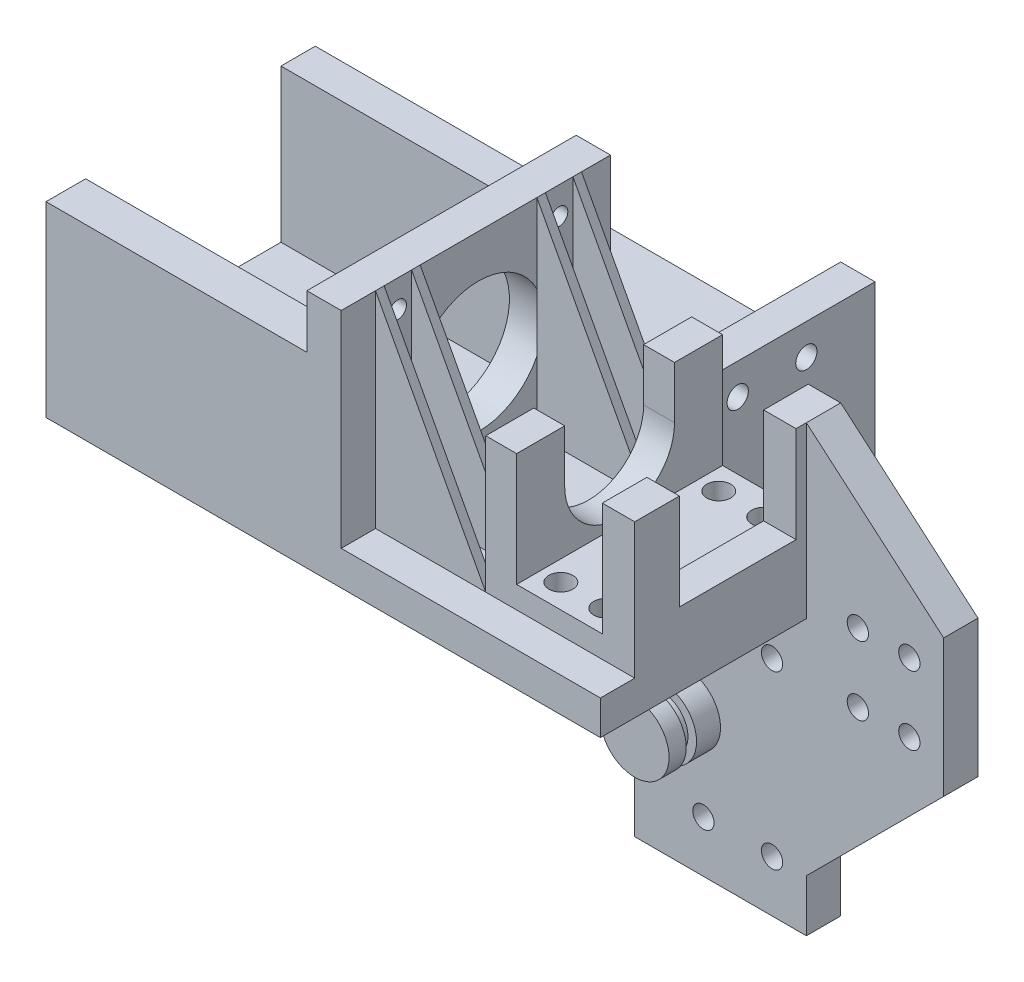
SolidWorks part; units mm, degrees
ref_plane "Front Plane" through (0, 0, 0) normal (0, 0, 1) x (1, 0, 0)
ref_plane "Top Plane" through (0, 0, 0) normal (0, 1, 0) x (1, 0, 0)
ref_plane "Right Plane" through (0, 0, 0) normal (1, 0, 0) x (0, 0, -1)
sketch "Sketch1" plane through (0, 0, 0) normal (0, 1, 0) x (1, 0, 0)
  line L0 (0, 0) -> (161.51, 0)
  line L1 (161.51, 0) -> (161.51, 70)
  line L2 (161.51, 70) -> (121.51, 70)
  line L3 (121.51, 70) -> (121.51, 120)
  line L4 (121.51, 120) -> (0, 120)
  line L5 (0, 120) -> (0, 0)
  dimension "D1" = 40
  dimension "D2" = 161.51
  dimension "D3" = 70
  dimension "D4" = 120
extrude "Boss-Extrude1" add sketch "Sketch1" along normal blind 10
sketch "Sketch2" plane through (0, 10, 0) normal (0, 1, 0) x (1, 0, 0)
  line L1 (161.51, 70) -> (152.06, 70)
  line L2 (161.51, 70) -> (161.51, 10)
  line L3 (161.51, 10) -> (152.06, 10)
  line L4 (152.06, 70) -> (152.06, 10)
  line L5 (0, 0) -> (161.51, 0) construction
  dimension "D1" = 9.45
  dimension "D2" = 10
extrude "Boss-Extrude2" add sketch "Sketch2" along normal blind 39.45
sketch "Sketch3" plane through (0, 10, 0) normal (0, 1, 0) x (1, 0, 0)
  line L1 (152.06, 70) -> (127.1, 70)
  line L2 (152.06, 70) -> (152.06, 10)
  line L3 (152.06, 10) -> (127.1, 10)
  line L4 (127.1, 70) -> (127.1, 10)
  line L5 (0, 0) -> (161.51, 0) construction
  dimension "D1" = 24.96
  dimension "D2" = 10
extrude "Boss-Extrude3" add sketch "Sketch3" along normal blind 6.45
sketch "Sketch4" plane through (0, 10, 0) normal (0, 1, 0) x (1, 0, 0)
  line L1 (127.1, 70) -> (118.1, 70)
  line L2 (127.1, 70) -> (127.1, 10)
  line L3 (127.1, 10) -> (118.1, 10)
  line L4 (118.1, 70) -> (118.1, 10)
  line L5 (0, 0) -> (161.51, 0) construction
  dimension "D1" = 9
  dimension "D2" = 10
extrude "Boss-Extrude4" add sketch "Sketch4" along normal blind 39.45
sketch "Sketch5" plane through (161.51, 0, 0) normal (1, 0, 0) x (0, 0, -1)
  line L0 (10, 49.45) -> (70, 49.45) construction
  line L1 (23, 49.45) -> (57, 49.45)
  line L2 (23, 49.45) -> (23, 21.45)
  line L3 (23, 21.45) -> (57, 21.45)
  line L4 (57, 49.45) -> (57, 21.45)
  line L5 (10, 49.45) -> (10, 10) construction
  point P11 (30, 49.45)
  dimension "D1" = 34
  dimension "D2" = 28
  dimension "D3" = 13
extrude "Cut-Extrude1" cut sketch "Sketch5" against normal up to next
sketch "Sketch6" plane through (127.1, 0, 0) normal (1, 0, 0) x (0, 0, -1)
  line L0 (24, 49.45) -> (24, 34.24)
  line L1 (10, 49.45) -> (70, 49.45) construction
  line L2 (56, 49.45) -> (56, 34.24)
  line L3 (40, 49.45) -> (40, 0) construction
  line L5 (24, 49.45) -> (56, 49.45)
  line L8 (10, 49.45) -> (70, 49.45) construction
  line L9 (0, 0) -> (70, 0) construction
  arc A0 (24, 34.24) -> (56, 34.24) centre (40, 34.24) ccw
  point P5 (0, 0)
  dimension "D2" = 16
  dimension "D1" = 15.21
extrude "Cut-Extrude2" cut sketch "Sketch6" against normal up to next
sketch "Sketch7" plane through (0, 10, 0) normal (0, 1, 0) x (1, 0, 0)
  line L1 (0, 11.55) -> (76, 11.55)
  line L2 (0, 11.55) -> (0, 0)
  line L3 (0, 0) -> (76, 0)
  line L4 (76, 11.55) -> (76, 0)
  line L5 (0, 120) -> (0, 0) construction
  point P5 (0, 0)
  point P7 (0, 0)
  point P9 (0, 0)
  dimension "D1" = 11.55
  dimension "D2" = 76
extrude "Boss-Extrude5" add sketch "Sketch7" along normal blind 44.46
sketch "Sketch8" plane through (0, 10, 0) normal (0, 1, 0) x (1, 0, 0)
  line L0 (0, 120) -> (0, 11.55) construction
  line L1 (0, 78.45) -> (76, 78.45)
  line L2 (0, 78.45) -> (0, 68.45)
  line L3 (0, 68.45) -> (76, 68.45)
  line L4 (76, 78.45) -> (76, 68.45)
  line L5 (76, 11.55) -> (0, 11.55) construction
  dimension "D1" = 76
  dimension "D2" = 10
  dimension "D3" = 56.9
extrude "Boss-Extrude6" add sketch "Sketch8" along normal blind 44.46
sketch "Sketch9" plane through (0, 10, 0) normal (0, 1, 0) x (1, 0, 0)
  line L1 (76, 78.45) -> (86, 78.45)
  line L2 (76, 78.45) -> (76, 0)
  line L3 (76, 0) -> (86, 0)
  line L4 (86, 78.45) -> (86, 0)
  point P5 (0, 0)
  dimension "D1" = 10
extrude "Boss-Extrude7" add sketch "Sketch9" along normal blind 60
sketch "Sketch10" plane through (86, 0, 0) normal (1, 0, 0) x (0, 0, -1)
  line L0 (0, 70) -> (78.45, 70) construction
  line L1 (70, 70) -> (67.5, 70)
  line L2 (70, 70) -> (70, 10)
  line L3 (70, 10) -> (67.5, 10)
  line L4 (67.5, 70) -> (67.5, 10)
  line L5 (70, 10) -> (120, 10) construction
  line L6 (0, 10) -> (78.45, 10) construction
  line L7 (59.5, 70) -> (57, 70)
  line L8 (59.5, 70) -> (59.5, 10)
  line L9 (59.5, 10) -> (57, 10)
  line L10 (57, 70) -> (57, 10)
  line L12 (23, 70) -> (20.5, 70)
  line L13 (23, 70) -> (23, 10)
  line L14 (23, 10) -> (20.5, 10)
  line L15 (20.5, 70) -> (20.5, 10)
  line L16 (10, 70) -> (12.5, 70)
  line L17 (10, 70) -> (10, 10)
  line L18 (10, 10) -> (12.5, 10)
  line L19 (12.5, 70) -> (12.5, 10)
  line L20 (0, 70) -> (0, 10) construction
  dimension "D1" = 10
  dimension "D2" = 2.5
  dimension "D3" = 8
  dimension "D4" = 2.5
  dimension "D5" = 34
  dimension "D6" = 2.5
  dimension "D7" = 8
  dimension "D8" = 2.5
extrude "Boss-Extrude8" add sketch "Sketch10" along normal up to surface (32.1 mm away) up to face at (118.1, 33.785, -40)
sketch "Sketch13" plane through (0, 0, -70) normal (0, 0, -1) x (-1, 0, 0)
  line L0 (-111.51, 0) -> (-161.51, 0)
  line L1 (-121.51, 0) -> (0, 0) construction
  line L2 (-161.51, 0) -> (-161.51, 49.45)
  line L3 (-161.51, 49.45) -> (-201.51, 15.1537)
  line L4 (-201.51, 15.1537) -> (-201.51, -24.8463)
  line L5 (-201.51, -24.8463) -> (-161.51, -64.85)
  line L6 (-161.51, -64.85) -> (-161.51, -80)
  line L7 (-161.51, -80) -> (-111.51, -80)
  line L8 (-111.51, -80) -> (-111.51, 0)
  point P5 (-205.8086, -29.1354)
  point P13 (-159.8496, -66.225)
  dimension "D1" = 80
  dimension "D2" = 15.15
  dimension "D3" = 40
  dimension "D4" = 52.69
  dimension "D5" = 90
  dimension "D7" = 50
  dimension "D8" = 40
extrude "Boss-Extrude12" add sketch "Sketch13" against normal blind 10
sketch "Sketch16" plane through (0, 0, -70) normal (0, 0, -1) x (-1, 0, 0)
  line L0 (-86, 70) -> (-118.1, 70)
  line L1 (-118.1, 70) -> (-118.1, 10)
  line L2 (-121.51, 10) -> (-86, 10) construction
  line L3 (-118.1, 10) -> (-86, 70)
extrude "Cut-Extrude5" cut sketch "Sketch16" against normal through all
sketch "Sketch17" plane through (0, 0, 0) normal (0, -1, 0) x (1, 0, 0)
  line L1 (111.51, -70) -> (121.51, -70)
  line L2 (111.51, -70) -> (111.51, -120)
  line L3 (111.51, -120) -> (121.51, -120)
  line L4 (121.51, -70) -> (121.51, -120)
extrude "Boss-Extrude13" add sketch "Sketch17" along normal up to surface (80 mm away) up to face at (136.51, -80, -65)
sketch "Sketch18" plane through (0, 10, 0) normal (0, 1, 0) x (1, 0, 0)
  line L0 (118.1, 70) -> (86, 70) construction
  line L1 (121.51, 120) -> (111.51, 120)
  line L2 (121.51, 120) -> (121.51, 70)
  line L3 (121.51, 70) -> (111.51, 70)
  line L4 (111.51, 120) -> (111.51, 70)
  dimension "D1" = 10
extrude "Boss-Extrude14" add sketch "Sketch18" along normal blind 25
sketch "Sketch19" plane through (0, 16.45, 0) normal (0, 1, 0) x (1, 0, 0)
  line L0 (152.06, 70) -> (127.1, 70) construction
  line L1 (161.51, 10) -> (161.51, 23) construction
  circle A0 centre (146.1, 62.98) radius 3.5
  circle A1 centre (133, 62.98) radius 3.5
  circle A2 centre (133, 16.98) radius 3.5
  circle A3 centre (146.1, 16.98) radius 3.5
  point P8 (0, 0)
  point P9 (0, 0)
  point P10 (0, 0)
  point P11 (0, 0)
  point P12 (0, 0)
  dimension "D1" = 7
  dimension "D2" = 7.02
  dimension "D3" = 46
  dimension "D4" = 13.1
  dimension "D5" = 15.41
extrude "Cut-Extrude6" cut sketch "Sketch19" against normal blind 20
sketch "Sketch20" plane through (0, 0, -60) normal (0, 0, 1) x (1, 0, 0)
  line L0 (111.51, 0) -> (131.1644, 0) construction
  line L1 (126.1, 0) -> (153.1, 0)
  line L2 (126.1, 0) -> (126.1, -6)
  line L3 (126.1, -6) -> (153.1, -6)
  line L4 (153.1, 0) -> (153.1, -6)
  line L5 (111.51, -80) -> (111.51, 0) construction
  dimension "D1" = 14.59
  dimension "D2" = 27
  dimension "D3" = 6
extrude "Cut-Extrude7" cut sketch "Sketch20" against normal blind 10
sketch "Sketch21" plane through (76, 0, 0) normal (-1, 0, 0) x (0, 0, 1)
  line L0 (-78.45, 70) -> (0, 70) construction
  line L1 (-78.45, 70) -> (-78.45, 54.46) construction
  line L2 (-63.5, 61.95) -> (-16.5, 14.95) construction
  line L3 (-16.5, 61.95) -> (-63.5, 14.95) construction
  circle A0 centre (-16.5, 61.95) radius 2.51
  circle A1 centre (-63.5, 61.95) radius 2.51
  circle A2 centre (-63.5, 14.95) radius 2.51
  circle A3 centre (-16.5, 14.95) radius 2.51
  circle A4 centre (-40, 38.45) radius 19
  dimension "D1" = 5.02
  dimension "D6" = 38
  dimension "D2" = 8.05
  dimension "D3" = 14.95
  dimension "D4" = 47
  dimension "D5" = 47
extrude "Cut-Extrude8" cut sketch "Sketch21" against normal blind 10
sketch "Sketch22" plane through (0, 0, -70) normal (0, 0, -1) x (-1, 0, 0)
  line L0 (-161.51, -80) -> (-121.51, -80) construction
  line L1 (-121.51, 35) -> (-121.51, -80) construction
  line L2 (-201.51, 15.1537) -> (-151.51, 15.1537) construction
  line L3 (-201.51, 15.1537) -> (-201.51, -24.8463) construction
  circle A0 centre (-131.51, -15) radius 3.1
  circle A1 centre (-151.51, -15) radius 3.1
  circle A2 centre (-151.51, -65) radius 3.1
  circle A3 centre (-131.51, -65) radius 3.1
  circle A4 centre (-191.51, 5.1537) radius 3.1
  circle A5 centre (-176.51, 5.1537) radius 3.1
  circle A6 centre (-176.51, -14.8463) radius 3.1
  circle A7 centre (-191.51, -14.8463) radius 3.1
  point P23 (0, 0)
  point P24 (0, 0)
  point P25 (0, 0)
  point P26 (0, 0)
  dimension "D4" = 6.2
  dimension "D6" = 6.2
  dimension "D1" = 20
  dimension "D2" = 15
  dimension "D3" = 50
  dimension "D5" = 10
  dimension "D7" = 15
  dimension "D8" = 20
  dimension "D9" = 10
  dimension "D10" = 10
extrude "Cut-Extrude9" cut sketch "Sketch22" against normal blind 10
sketch "Sketch23" plane through (111.51, 0, 0) normal (-1, 0, 0) x (0, 0, 1)
  line L0 (-120, 35) -> (-70, 35) construction
  line L2 (-120, -80) -> (-120, 0) construction
  circle A0 centre (-100, 25.93) radius 3.1
  circle A1 centre (-80, 25.93) radius 3.1
  circle A2 centre (-80, -15.01) radius 3.1
  circle A3 centre (-100, -15.01) radius 3.1
  circle A4 centre (-100, -65.01) radius 3.1
  circle A5 centre (-80, -65.01) radius 3.1
  point P12 (0, 0)
  point P13 (0, 0)
  point P14 (0, 0)
  point P15 (0, 0)
  point P16 (0, 0)
  dimension "D1" = 6.2
  dimension "D2" = 50
  dimension "D3" = 40.94
  dimension "D4" = 9.07
  dimension "D5" = 20
  dimension "D6" = 20
extrude "Cut-Extrude10" cut sketch "Sketch23" against normal blind 10
sketch "Sketch24" plane through (0, 0, -60) normal (0, 0, 1) x (1, 0, 0)
  line L0 (161.51, -80) -> (111.51, -80) construction
  line L1 (111.51, -80) -> (111.51, 0) construction
  circle A0 centre (126.51, -40) radius 10
  dimension "D3" = 20
  dimension "D1" = 40
  dimension "D2" = 15
extrude "Boss-Extrude15" add sketch "Sketch24" along normal blind 15
sketch "Sketch25" plane through (0, 0, -45) normal (0, 0, 1) x (1, 0, 0)
  line L0 (126.51, -30) -> (126.51, -50) construction
  circle A0 centre (126.51, -40) radius 10 construction
  circle A1 centre (126.51, -40) radius 10 construction
  circle A2 centre (126.51, -40) radius 10
  circle A3 centre (126.51, -40) radius 7.5
  dimension "D1" = 20
  dimension "D2" = 15
extrude "Cut-Extrude11" cut sketch "Sketch25" against normal blind 3 from offset 5 offset against normal yes
sketch "Sketch26" plane through (111.51, 0, 0) normal (-1, 0, 0) x (0, 0, 1)
  line L0 (-60, -80) -> (-120, -80) construction
  line L1 (-60, -80) -> (-60, 0) construction
  circle A0 centre (-75, -40) radius 10
  dimension "D3" = 20
  dimension "D1" = 40
  dimension "D2" = 15
extrude "Boss-Extrude16" add sketch "Sketch26" along normal blind 15
sketch "Sketch27" plane through (96.51, 0, 0) normal (-1, 0, 0) x (0, 0, 1)
  line L0 (-75, -30) -> (-75, -50) construction
  circle A0 centre (-75, -40) radius 10 construction
  circle A1 centre (-75, -40) radius 10 construction
  circle A2 centre (-75, -40) radius 10
  circle A3 centre (-75, -40) radius 7.5
  point P9 (-75, -40)
  dimension "D1" = 20
  dimension "D2" = 15
extrude "Cut-Extrude12" cut sketch "Sketch27" against normal blind 3 from offset 5
